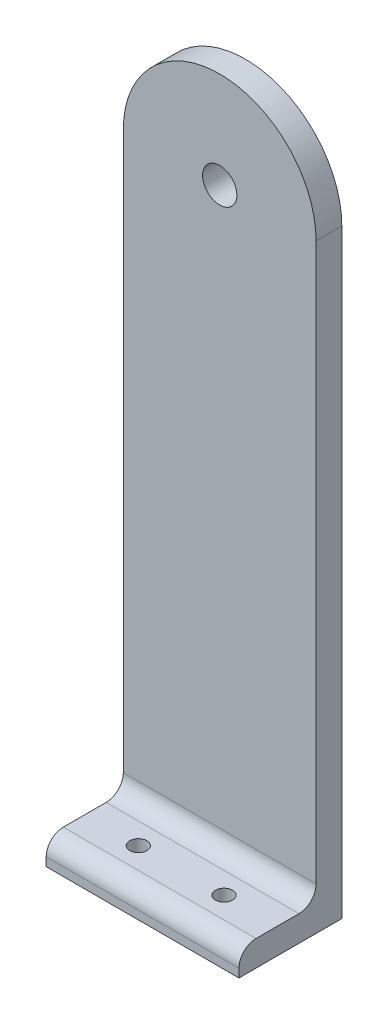
SolidWorks part; units mm, degrees
material "ABS"
ref_plane "Front Plane" through (0, 0, 0) normal (0, 0, 1) x (1, 0, 0)
ref_plane "Top Plane" through (0, 0, 0) normal (0, 1, 0) x (1, 0, 0)
ref_plane "Right Plane" through (0, 0, 0) normal (1, 0, 0) x (0, 0, -1)
sketch "Sketch1" plane through (0, 0, 0) normal (0, 0, 1) x (1, 0, 0)
  line L0 (-28.575, 0) -> (-28.575, -177.8)
  line L1 (-28.575, -177.8) -> (28.575, -177.8)
  line L2 (28.575, -177.8) -> (28.575, 0)
  arc A0 (-28.575, 0) -> (28.575, 0) centre (0, 0) cw
  dimension "D1" = 28.575
  dimension "D2" = 177.8
extrude "Boss-Extrude1" add sketch "Sketch1" along normal blind 7.62
sketch "Sketch2" plane through (-28.575, 0, 0) normal (-1, 0, 0) x (0, 0, 1)
  line L1 (0, -177.8) -> (30.48, -177.8)
  line L2 (0, -177.8) -> (0, -170.18)
  line L3 (0, -170.18) -> (25.4, -170.18)
  line L4 (30.48, -177.8) -> (30.48, -175.26)
  arc A0 (25.4, -170.18) -> (30.48, -175.26) centre (25.4, -175.26) cw
  point P7 (30.48, -170.18)
  dimension "D3" = 5.08
  dimension "D1" = 7.62
  dimension "D2" = 30.48
extrude "Boss-Extrude2" add sketch "Sketch2" against normal through all
fillet "Fillet1" radius 5.08 1 edges at (0, -170.18, 7.62)
sketch "Sketch3" plane through (0, -170.18, 0) normal (0, 1, 0) x (1, 0, 0)
  line L0 (-28.575, -25.4) -> (-28.575, -12.7) construction
  circle A0 centre (12.7, -19.05) radius 2.54
  circle A1 centre (-12.7, -19.05) radius 2.54
  dimension "D1" = 5.08
  dimension "D2" = 5.08
  dimension "D3" = 25.4
  dimension "D4" = 15.875
extrude "Cut-Extrude1" cut sketch "Sketch3" against normal through all
sketch "Sketch4" plane through (0, 0, 0) normal (0, 0, -1) x (-1, 0, 0)
  line L0 (-28.575, -177.8) -> (-28.575, 0) construction
  line L1 (28.575, 0) -> (28.575, -177.8) construction
  circle A0 centre (0, 0) radius 5.08
  arc A1 (28.575, 0) -> (-28.575, 0) centre (0, 0) ccw construction
  dimension "D1" = 10.16
  dimension "D2" = 28.575
  dimension "D3" = 28.575
  dimension "D4" = 0
extrude "Cut-Extrude2" cut sketch "Sketch4" against normal through all
